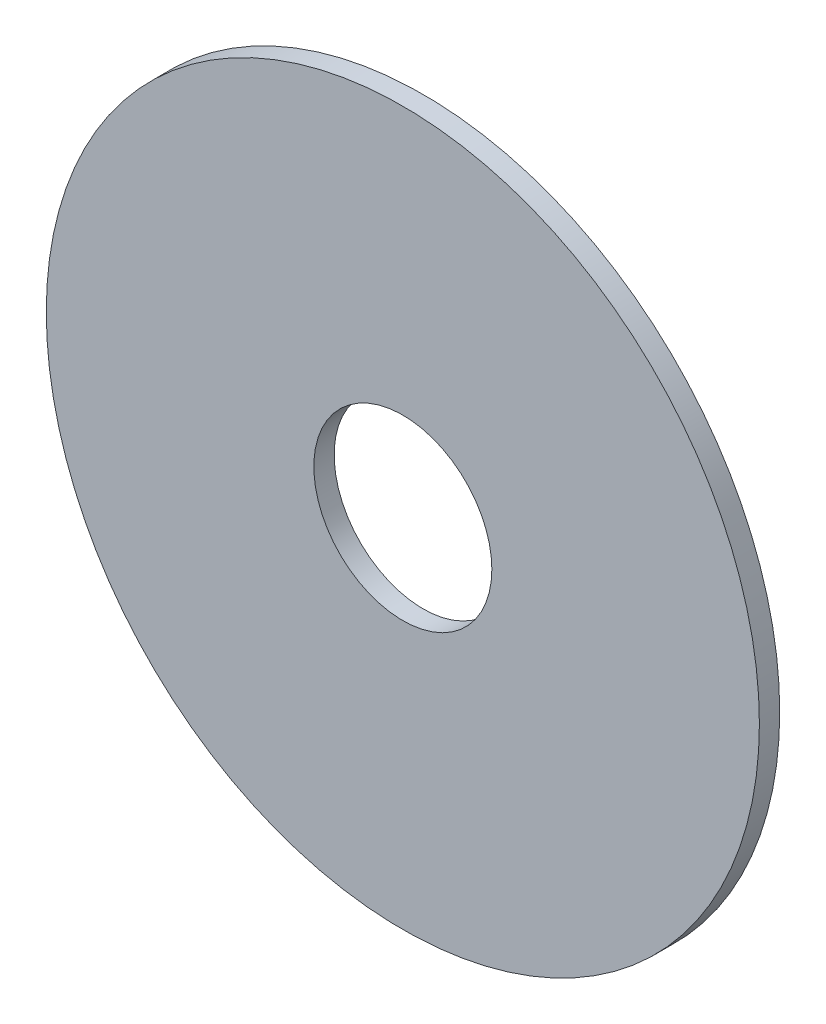
SolidWorks part; units mm, degrees
material "Stainless Steel (ferritic)"
ref_plane "Front Plane" through (0, 0, 0) normal (0, 0, 1) x (1, 0, 0)
ref_plane "Top Plane" through (0, 0, 0) normal (0, 1, 0) x (1, 0, 0)
ref_plane "Right Plane" through (0, 0, 0) normal (1, 0, 0) x (0, 0, -1)
sketch "Sketch1" plane through (0, 0, 0) normal (0, 0, 1) x (1, 0, 0)
  circle A0 centre (0, 0) radius 25.435
  circle A1 centre (0, 0) radius 6.35
  dimension "D1" = 50.87
  dimension "D2" = 12.7
extrude "Boss-Extrude1" add sketch "Sketch1" along normal mid plane 1.45
